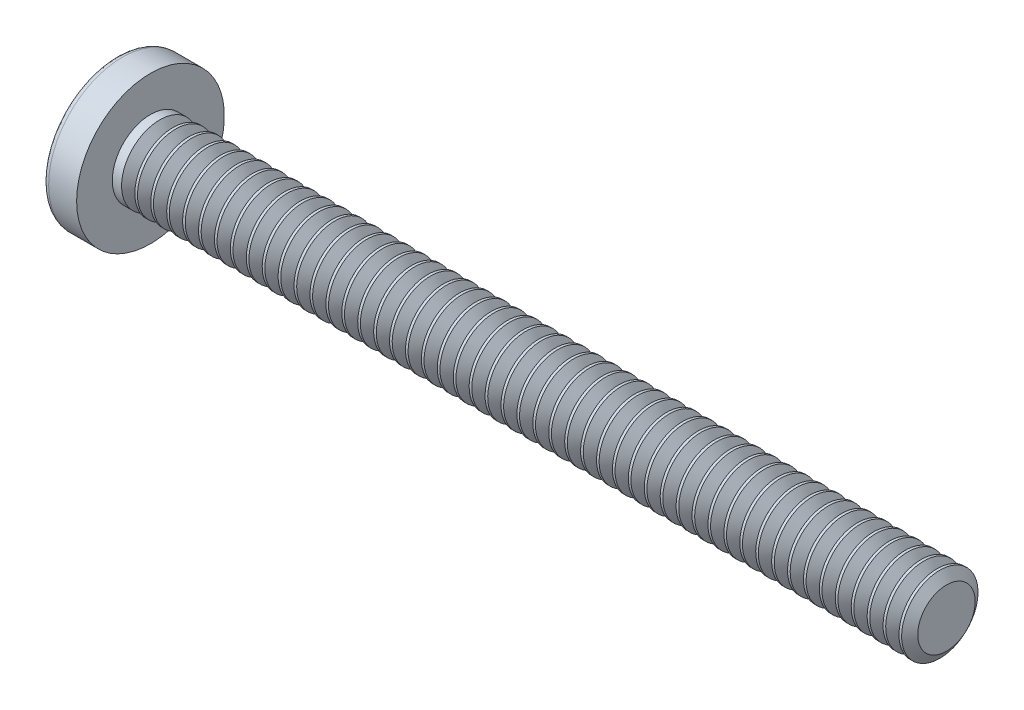
SolidWorks part; units mm, degrees
ref_plane "Plane1" through (0, 0, 0) normal (0, 0, 1) x (1, 0, 0)
ref_plane "Plane2" through (0, 0, 0) normal (0, 1, 0) x (1, 0, 0)
ref_plane "Plane3" through (0, 0, 0) normal (1, 0, 0) x (0, 0, -1)
other "Configuration Table"
sketch "BodySke" plane through (0, 0, 0) normal (0, 0, 1) x (1, 0, 0)
  line L0 (1.1176, 0.762) -> (1.1176, 1.4732)
  line L1 (1.2763, 6.35) -> (1.2764, -3.175) construction
  line L2 (-25.4, 0) -> (127, 0) construction
  line L3 (16.9926, 0) -> (0, 0)
  line L4 (1.1176, 0.762) -> (16.9926, 0.762)
  line L5 (16.9926, 0.762) -> (16.9926, 0)
  line L6 (0.5595, 1.4732) -> (1.1176, 1.4732)
  line L7 (1.1176, -0.762) -> (16.9926, -0.762) construction
  line L8 (1.1176, 6.35) -> (1.1176, -3.175) construction
  arc A0 (0.4562, 1.4202) -> (0, 0) centre (2.4384, 0) ccw
  arc A2 (0.4562, 1.4202) -> (0.5595, 1.4732) centre (0.5595, 1.3462) cw
  dimension "Head_crown_rad" = 2.4384
  dimension "Head_fillet_rad" = 0.127
  dimension "Diameter" = 1.524
  dimension "Length" = 15.875
  dimension "Head_ht" = 1.1176
  dimension "Head_dia" = 2.9464
  dimension "Advance" = 0.3175
  dimension "Thread_nom" = 15.875
revolve "Base-Revolve" add sketch "BodySke" angle 360 about L2
cosmetic thread "ThreadCosmetic" [suppressed] parameters "Thread_length"=15.5575, "Thread_minor"=1.1455
sketch "Sketch3" plane through (0, 0, 0) normal (1, 0, 0) x (0, 0, -1)
  line L0 (0.2794, -0.9652) -> (-0.2794, -0.9652)
  line L1 (0.2794, -0.9652) -> (0.2794, 0.9652)
  line L2 (-0.2794, 0.9652) -> (0.2794, 0.9652)
  line L3 (-0.2794, 0.9652) -> (-0.2794, -0.9652)
  dimension "Cross_dia" = 1.9304
  dimension "D1" = 0.9652
  dimension "Cross_width" = 0.5588
  dimension "D2" = 0.2794
ref_plane "Plane4" through (0.9652, 0, 0) normal (1, 0, 0) x (0, 0, -1)
sketch "Sketch4" plane through (0.9652, 0, 0) normal (1, 0, 0) x (0, 0, -1)
  line L0 (0.1397, -0.1397) -> (-0.1397, -0.1397)
  line L1 (0.1397, -0.1397) -> (0.1397, 0.1397)
  line L2 (-0.1397, 0.1397) -> (0.1397, 0.1397)
  line L3 (-0.1397, 0.1397) -> (-0.1397, -0.1397)
  dimension "D2" = 0.2794
  dimension "D1" = 0.2794
  dimension "D3" = 0.1397
  dimension "D4" = 0.1397
loft "Cut-Loft1" cut profiles "Sketch3", "Sketch4"
pattern_circular "CirPattern1" count 2 every 90 about axis through (0, 0, 0) along (1, 0, 0) of "Cut-Loft1"
sketch "ThdSchSke" plane through (0, 0, 0) normal (0, 0, 1) x (1, 0, 0)
  line L0 (1.4351, -0.5728) -> (1.3026, -0.762)
  line L1 (1.4351, -0.5728) -> (1.5676, -0.762)
  line L2 (1.5676, -0.762) -> (1.5676, -0.9525)
  line L3 (-3.175, 0) -> (5.1513, 0) construction
  line L5 (1.5676, -0.9525) -> (1.3026, -0.9525)
  line L6 (1.3026, -0.9525) -> (1.3026, -0.762)
  dimension "Diameter" = 1.524
  dimension "SideAngle" = 55
  dimension "VeeAngle" = 70
  dimension "Thread_minor" = 1.1455
  dimension "Overcut" = 1.905
  dimension "Start" = 1.4351
revolve "ThreadSchematic" cut sketch "ThdSchSke" angle 360 about L3
pattern_linear "ThdSchPat" count 50 spacing 0.3175 along (1, 0, 0) of "ThreadSchematic"
equation "\"D1@Sketch3\" = \"Cross_dia@Sketch3\" / 2"
equation "\"D2@Sketch3\" = \"Cross_width@Sketch3\" / 2"
equation "\"D1@Sketch4\" = \"Cross_width@Sketch3\" *.5"
equation "\"D2@Sketch4\" = \"D1@Sketch4\""
equation "\"D3@Sketch4\" = \"D1@Sketch4\" / 2"
equation "\"D4@Sketch4\" = \"D2@Sketch4\" / 2"
equation "\"Thread_length@ThreadCosmetic\" = ((sgn( (\"Length@BodySke\" - \"Advance@BodySke\" ) - \"Thread_nom@BodySke\" )-1)*( (\"Length@BodySke\" - \"Advance@BodySke\" ) - \"Thread_nom@BodySke\" ))/-2+ \"Thread_nom@BodySke\""
equation "\"Thread_minor@ThdSchSke\" = \"Thread_minor@ThreadCosmetic\""
equation "\"Diameter@ThdSchSke\" = \"Diameter@BodySke\""
equation "\"Overcut@ThdSchSke\" = \"Diameter@BodySke\" * 1.25"
equation "\"Start@ThdSchSke\" = \"Head_ht@BodySke\" + \"Length@BodySke\" - \"Thread_length@ThreadCosmetic\"  '---Non-countersunk---"
equation "\"Num_threads@ThdSchPat\" = int( \"Thread_length@ThreadCosmetic\" / \"Advance@BodySke\" + 0.999 )  + 1"
equation "\"Advance@ThdSchPat\" = \"Thread_length@ThreadCosmetic\" /  (\"Num_threads@ThdSchPat\" - 1) 'relax it"
